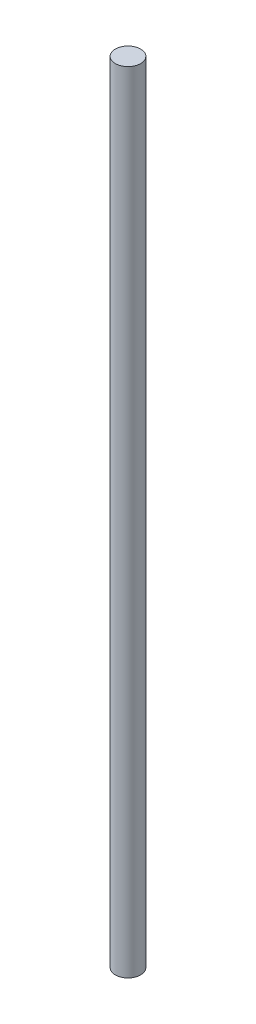
SolidWorks part; units mm, degrees
ref_plane "Front Plane" through (0, 0, 0) normal (0, 0, 1) x (1, 0, 0)
ref_plane "Top Plane" through (0, 0, 0) normal (0, 1, 0) x (1, 0, 0)
ref_plane "Right Plane" through (0, 0, 0) normal (1, 0, 0) x (0, 0, -1)
sketch "Sketch1" plane through (0, 0, 0) normal (0, 1, 0) x (1, 0, 0)
  circle A0 centre (0, 0) radius 4
extrude "Boss-Extrude4" add sketch "Sketch1" along normal blind 250
